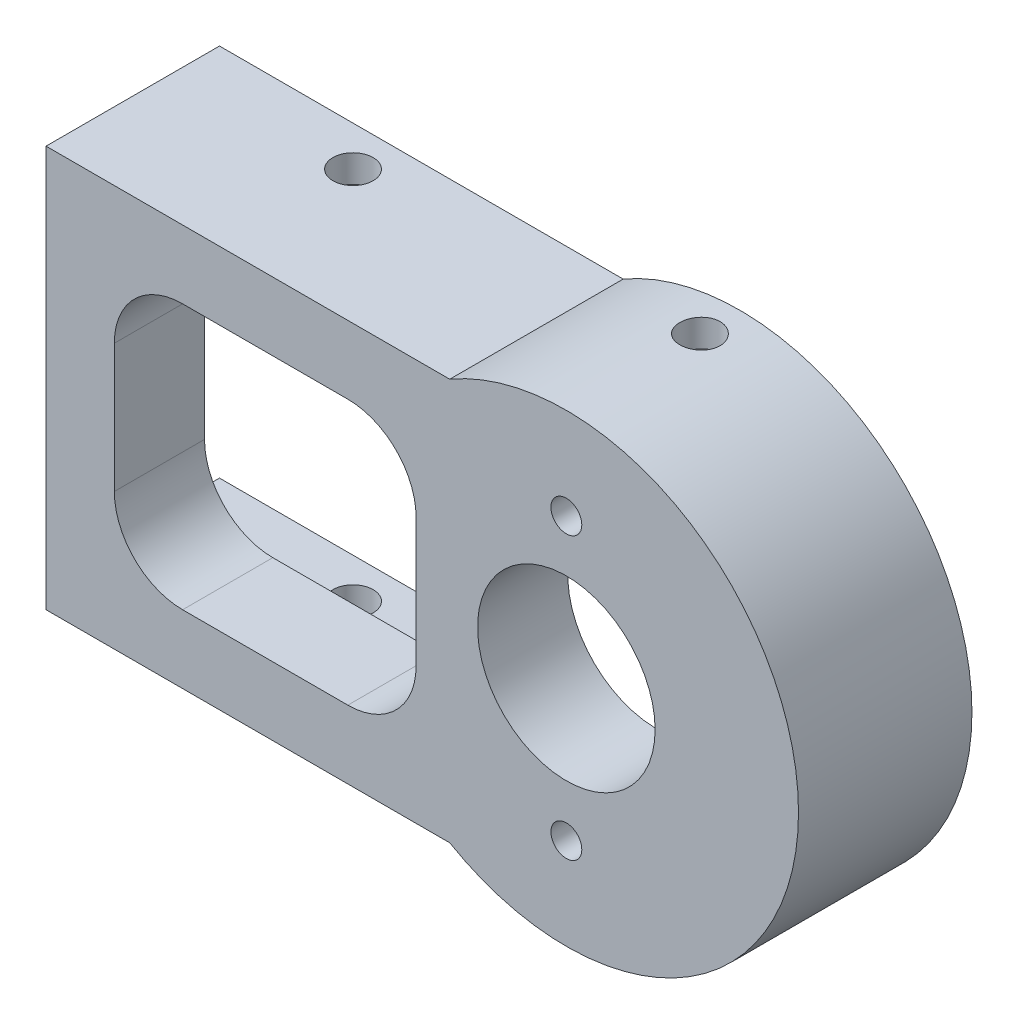
SolidWorks part; units mm, degrees
ref_plane "Front Plane" through (0, 0, 0) normal (0, 0, 1) x (1, 0, 0)
ref_plane "Top Plane" through (0, 0, 0) normal (0, 1, 0) x (1, 0, 0)
ref_plane "Right Plane" through (0, 0, 0) normal (1, 0, 0) x (0, 0, -1)
sketch "Sketch2" plane through (0, 0, 0) normal (0, 0, 1) x (1, 0, 0)
  line L0 (-38.1, -14.7) -> (0, -14.7) construction
  line L1 (-38.1, -14.7) -> (-38.1, 14.7)
  line L3 (-38.1, 14.7) -> (0, 14.7) construction
  line L4 (-38.1, -14.7) -> (0, 14.7) construction
  line L5 (0, -14.7) -> (-38.1, 14.7) construction
  line L6 (0, 0) -> (-63.6035, 0) construction
  line L7 (-38.1, 14.7) -> (-8.5387, 14.7)
  line L8 (-8.5387, -14.7) -> (-38.1, -14.7)
  line L9 (0, 10.2947) -> (0, -10.2947) construction
  line L10 (0, 14.7) -> (0, -14.7) construction
  line L12 (-11, 9.7) -> (-33.1, 9.7)
  line L13 (-11, 9.7) -> (-11, -9.7)
  line L14 (-11, -9.7) -> (-33.1, -9.7)
  line L15 (-33.1, 9.7) -> (-33.1, -9.7)
  line L16 (-11, 9.7) -> (-33.1, -9.7) construction
  line L17 (-11, -9.7) -> (-33.1, 9.7) construction
  circle A0 centre (0, 0) radius 17 construction
  arc A1 (-8.5387, -14.7) -> (-8.5387, 14.7) centre (0, 0) ccw
  circle A2 centre (0, 0) radius 6.5
  circle A3 centre (0, -10.2947) radius 1.1303
  circle A4 centre (0, 10.2947) radius 1.1303
  point P3 (-38.1, 0)
  point P4 (-19.05, 0)
  point P11 (-22.05, 0)
  point P20 (0, 0)
  point P24 (-11, 0)
  dimension "D1" = 34
  dimension "D4" = 13
  dimension "D5" = 2.2606
  dimension "D2" = 29.4
  dimension "D3" = 38.1
  dimension "D6" = 5
  dimension "D7" = 11
  dimension "D8" = 5
extrude "Boss-Extrude1" add sketch "Sketch2" along normal blind 12.7
sketch "Sketch1" plane through (0, 0, 0) normal (0, 0, 1) x (1, 0, 0)
  line L0 (-38.1, -12.7) -> (0, -12.7) construction
  line L1 (-38.1, -12.7) -> (-38.1, 12.7)
  line L2 (0, -12.7) -> (0, 12.7) construction
  line L3 (-38.1, 12.7) -> (0, 12.7) construction
  line L4 (-38.1, -12.7) -> (0, 12.7) construction
  line L5 (0, -12.7) -> (-38.1, 12.7) construction
  line L6 (-20.0762, 0) -> (0, 0) construction
  line L7 (-38.1, 14.7) -> (-38.1, -14.7) construction
  line L8 (-7.9819, 12.7) -> (-38.1, 12.7)
  line L9 (-7.9819, -12.7) -> (-38.1, -12.7)
  circle A1 centre (0, 0) radius 15 construction
  arc A2 (-7.9819, -12.7) -> (-7.9819, 12.7) centre (0, 0) ccw
  point P5 (-19.05, 0)
  point P7 (-38.1, 0)
  point P12 (0, 0)
  dimension "D1" = 30
  dimension "D2" = 25.4
extrude "Cut-Extrude1" cut sketch "Sketch1" along normal blind 6.096
ref_plane "Plane3" through (0, -17, 0) normal (0, -1, 0) x (-1, 0, 0)
sketch "Sketch6" plane through (0, -17, 0) normal (0, -1, 0) x (-1, 0, 0)
  line L0 (0, 0) -> (0, -2.921) construction
  line L2 (7.9819, -6.096) -> (-15, -6.096) construction
  circle A0 centre (0, -2.921) radius 1.4732
  circle A1 centre (25.4, -2.921) radius 1.4732
  dimension "D2" = 2.9464
  dimension "D1" = 3.175
  dimension "D3" = 25.4
fillet "Fillet1" radius 5 4 edges at (-33.1, 9.7, 9.398) (-11, 9.7, 9.398) (-33.1, -9.7, 9.398) (-11, -9.7, 9.398)
extrude "Cut-Extrude4" cut sketch "Sketch6" against normal through all
equation "\"Drill4_40\"=2.9464"
equation "\"Tap4_40\"=2.2606"
equation "\"D5@Sketch2\"=\"Tap4_40\""
equation "\"D2@Sketch6\"=\"Drill4_40\""
